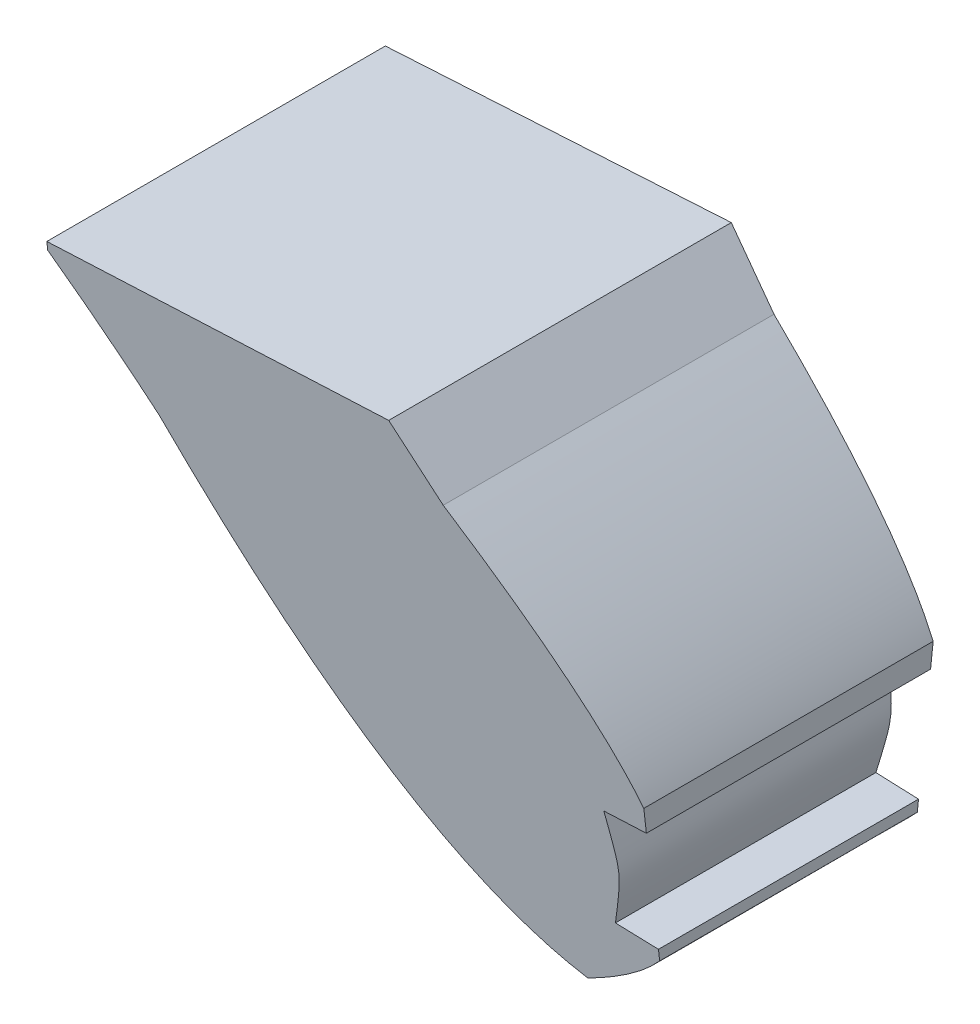
SolidWorks part; units mm, degrees
ref_plane "Alzado" through (0, 0, 0) normal (0, 0, 1) x (1, 0, 0)
ref_plane "Planta" through (0, 0, 0) normal (0, 1, 0) x (1, 0, 0)
ref_plane "Vista lateral" through (0, 0, 0) normal (1, 0, 0) x (0, 0, -1)
sketch "Croquis1" plane through (0, 0, 0) normal (0, 0, 1) x (1, 0, 0)
  line L0 (-8.9818, 12.6082) -> (-23.0359, 11.8716) construction
  line L1 (-8.9818, 12.6082) -> (-23.0359, 11.8716)
  line L2 (-8.9818, 12.6082) -> (-23.0359, 11.8716) construction
  line L4 (-8.9818, 12.6082) -> (-23.0359, 11.8716)
  line L6 (-1.3949, 1.9763) -> (0.3551, 2.2848) construction
  line L7 (-1.3949, 1.9763) -> (0.3551, 2.2848)
  line L8 (0.3551, 2.2848) -> (0.3551, 2.8423) construction
  line L9 (0.3551, 2.2848) -> (0.3551, 3.0015)
  line L10 (0.3551, -2.2848) -> (-1.3949, -2.2237) construction
  line L11 (0.3551, -2.2848) -> (-1.3949, -2.2237)
  line L12 (0.3551, 2.2848) -> (0.3551, -2.2848) construction
  line L13 (0.3551, -2.2848) -> (0.3551, -2.7233)
  line L14 (-8.9818, 12.6082) -> (-6.9949, 10.4774)
  line L15 (-23.0359, 11.5401) -> (-23.0359, 11.8716) construction
  line L16 (-23.0359, 11.5401) -> (-23.0359, 11.8716)
  arc A0 (-18.9452, 7.5409) -> (-23.0359, 11.5401) centre (-69.8841, -40.4718) ccw construction
  arc A1 (-18.9452, 7.5409) -> (-23.0359, 11.5401) centre (-69.8841, -40.4718) ccw
  spline S1 degree 2 poles (-828.7061, 3922.2202) (545.889, -3962.7836) (-262.0834, 3982.5902) knots 0.462185 0.462185 0.462185 0.537731 0.537731 0.537731 weights 1 1 1 only from (-18.9452, 7.5409) to (-2.8466, -5.0591) construction
  spline S2 degree 2 poles (-18.9452, 7.5409) (-10.215, -3.6976) (-2.8466, -5.0591) knots 0.497667 0.497667 0.497667 0.499554 0.499554 0.499554 weights 1 1 1
  spline S3 degree 2 poles (-3804.8689, 1232.5771) (3762.9122, -1369.6643) (-3716.5752, 1504.852) knots 0.462212 0.462212 0.462212 0.537836 0.537836 0.537836 weights 1 1 1 only from (0.3551, 3.0015) to (-6.9949, 10.4774) construction
  spline S4 degree 2 poles (0.3551, 3.0015) (-1.4487, 6.0584) (-6.9949, 10.4774) knots 0.500821 0.500821 0.500821 0.502013 0.502013 0.502013 weights 1 1 1
  spline S5 degree 2 poles (-1.3949, -2.2237) (-0.9075, -0.1237) (-1.3949, 1.9763) knots 0 0 0 1 1 1 weights 1 3.231801 1 construction
  spline S6 degree 2 poles (-1.3949, -2.2237) (-0.9075, -0.1237) (-1.3949, 1.9763) knots 0 0 0 1 1 1 weights 1 3.231801 1
  spline S7 degree 2 poles (-3997.263, 185.0077) (3984.2333, -348.7483) (-3965.0625, 511.2595) knots 0.462205 0.462205 0.462205 0.537778 0.537778 0.537778 weights 1 1 1 only from (-2.8466, -5.0591) to (0.3551, -2.7233) construction
  spline S8 degree 2 poles (-2.8466, -5.0591) (-0.7424, -3.9352) (0.3551, -2.7233) knots 0.498812 0.498812 0.498812 0.499413 0.499413 0.499413 weights 1 1 1
extrude "Saliente-Extruir1" add sketch "Croquis1" along normal mid plane 14 contours S2 S8 L13 L11 S6 L7 L9 S4 L14 L1 L16 A1
sketch "Croquis3" plane through (0, 0, 0) normal (0, 0, 1) x (1, 0, 0)
  line L0 (-6.742, 0) -> (0, 0) construction
  line L1 (-1.8181, 2) -> (-1.7771, 2.0103) construction
  line L3 (-1.8181, 2) -> (-0.1689, 2.4155) construction
  line L4 (-1.8181, 2) -> (0.3551, 3.0015)
  line L5 (0.3551, 3.0015) -> (0.3551, 0)
  line L6 (-1.9135, -2.1825) -> (0.3551, -2.2848)
  line L7 (0.3551, -2.2848) -> (0.3551, 0)
  parabola Q0 (-1.9135, -2.1825) -> (-1.8181, 2) focus (-3.3181, 0) apex (-1.3181, 0)
  dimension "D1" = 2
  dimension "D2" = 2
extrude "Cortar-Extruir1" [suppressed] cut sketch "Croquis3" against normal through all both and the other way through all
sketch "Croquis4" plane through (0, 0, 0) normal (0, 0, 1) x (1, 0, 0)
  line L0 (-1.3949, 1.9763) -> (0.3551, 2.2848) construction
  line L1 (-1.3949, 1.9763) -> (0.3551, 2.2848)
  line L2 (0.3551, 2.2848) -> (0.3551, 3.0015) construction
  line L3 (0.3551, 2.068) -> (0.3551, 2.2848)
  line L4 (-1.3949, 1.9763) -> (0.3551, 2.068)
  line L5 (0, 0) -> (-3.4665, 0) construction
  dimension "D1" = 3
extrude "Saliente-Extruir2" add sketch "Croquis4" along normal through all and the other way through all
sketch "Croquis7" plane through (0, 0, 0) normal (0, 0, 1) x (1, 0, 0)
  line L0 (0, 0) -> (-15.3945, 3.3171) construction
  line L1 (-17.3963, 18.9371) -> (-15.3945, 3.3171) construction
  line L2 (-15.3945, 3.3171) -> (-9.9316, -2.6296) construction
  line L3 (-15.3945, 3.3171) -> (-10.2385, 8.0535) construction
  line L4 (-17.3963, 18.9371) -> (-16.5429, 12.2783) construction
  line L5 (0, 0) -> (-1.3461, -2.2254) construction
  line L6 (-69.8841, 29.5282) -> (-81.9382, 42.5765) construction
  line L7 (-69.8841, 29.5282) -> (-20.9497, 29.5282) construction
  line L8 (-17.8101, 13.1658) -> (-25.5429, 13.1658)
  line L9 (-18.2059, 7.0951) -> (-21.9246, 11.9299) construction
  line L10 (0.3551, -2.5) -> (-2.4497, -2.0473)
  line L11 (-1.3461, -2.2254) -> (-2.0075, -3.6222) construction
  line L12 (-1.3461, -2.2254) -> (-1.4547, -2.8987) construction
  line L13 (-1.3461, -2.2254) -> (-1.2286, -1.4976) construction
  line L14 (0.3551, -2.2848) -> (0.3551, -2.7233) construction
  line L15 (0.3551, -2.2848) -> (-1.3949, -2.2237) construction
  line L16 (-2.0075, -3.6222) -> (-3.0629, -5.8512) construction
  line L17 (-2.6331, -4.9434) -> (-3.7044, -5.5324) construction
  line L18 (-2.6331, -4.9434) -> (-3.2248, -3.867) construction
  line L19 (-2.6331, -4.9434) -> (-2.2174, -6.1341) construction
  line L20 (-4.0838, -4.7637) -> (-1.6363, -5.0668) construction
  line L21 (-4.0838, -4.7637) -> (-0.036, -5.9454) construction
  line L22 (-4.0838, -4.7637) -> (-3.7621, -3.6616) construction
  line L23 (-4.0838, -4.7637) -> (-6.31, -3.7023) construction
  line L24 (-6.31, -3.7023) -> (-8.69, -2.5677) construction
  line L25 (-8.69, -2.5677) -> (-6.8421, -3.7725) construction
  line L26 (-8.69, -2.5677) -> (-7.9481, -1.4297) construction
  line L27 (-10.6884, -0.8477) -> (-8.69, -2.5677) construction
  line L28 (-10.6884, -0.8477) -> (-14.8546, 2.738) construction
  line L29 (-14.8546, 2.738) -> (-14.5337, 2.3989) construction
  line L30 (-14.8546, 2.738) -> (-14.6199, 2.9602) construction
  line L31 (-18.2059, 7.0951) -> (-14.8546, 2.738) construction
  line L32 (-8.9818, 12.6082) -> (-23.0359, 11.8716) construction
  line L33 (-8.9818, 12.6082) -> (-23.0359, 11.8716)
  line L34 (-21.9246, 11.9299) -> (-21.9826, 13.0367) construction
  line L35 (-21.9246, 11.9299) -> (-23.4156, 13.0367) construction
  arc A0 (-18.9452, 7.5409) -> (-23.0359, 11.5401) centre (-69.8841, -40.4718) ccw construction
  spline S0 degree 2 poles (-654.4568, 2937.5195) (409.3679, -2972.9237) (-163.476, 2987.5518) knots 0.467242 0.467242 0.467242 0.532662 0.532662 0.532662 weights 1 1 1 only from (-18.9452, 7.5409) to (-2.8466, -5.0591) construction
  spline S1 degree 2 poles (-18.6263, 7.1332) (-10.0803, -3.7225) (-2.8466, -5.0591) knots 0.497702 0.497702 0.497702 0.499554 0.499554 0.499554 weights 1 1 1 construction
  spline S3 degree 2 poles (-2999.4042, 119.7504) (2988.2948, -261.6206) (-2971.0465, 402.239) knots 0.467267 0.467267 0.467267 0.532713 0.532713 0.532713 weights 1 1 1 only from (-2.8466, -5.0591) to (0.3551, -2.7233) construction
  spline S4 degree 2 poles (-2.8466, -5.0591) (-2.7385, -5.0013) (-2.6331, -4.9434) knots 0.498812 0.498812 0.498812 0.498843 0.498843 0.498843 weights 1 1 1
  dimension "D1" = 2.5
  dimension "D2" = 22
  dimension "D3" = 16.17
  dimension "D4" = 54.138
  dimension "D5" = 34.566
  dimension "D6" = 50.413
sketch "Croquis6" plane through (0, 0, 0) normal (1, 0, 0) x (0, 0, -1)
  line L0 (7, 12.6082) -> (7, 10.4774) construction
  line L1 (7, 12.6082) -> (7, -5.0591)
  line L2 (-7, 12.6082) -> (-7, 10.4774) construction
  line L3 (-7, 12.6082) -> (-7, -5.0591)
  line L4 (-7, -5.0591) -> (7, -5.0591) construction
  line L5 (-7, -5.0591) -> (-5, -5.0591)
  line L6 (7, 12.6082) -> (5, -5.0591)
  line L7 (-7, 12.6082) -> (-5, -5.0591)
  line L8 (5, -5.0591) -> (7, -5.0591)
  dimension "D1" = 2
  dimension "D2" = 2
extrude "Cortar-Extruir2" cut sketch "Croquis6" against normal through all and the other way through all
